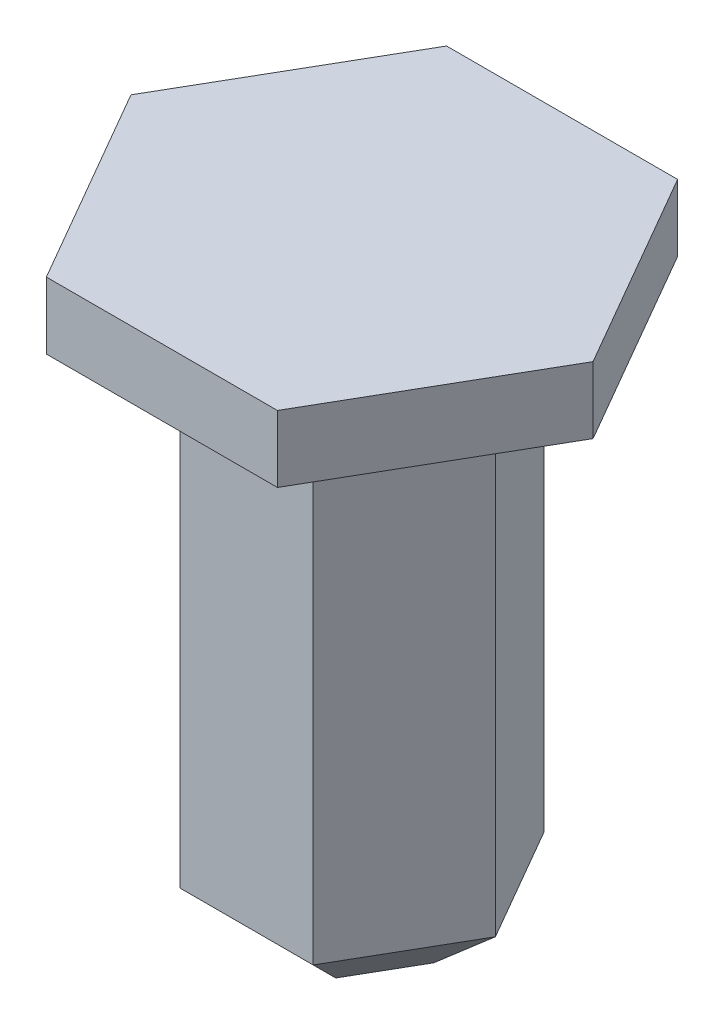
SolidWorks part; units mm, degrees
ref_plane "Front Plane" through (0, 0, 0) normal (0, 0, 1) x (1, 0, 0)
ref_plane "Top Plane" through (0, 0, 0) normal (0, 1, 0) x (1, 0, 0)
ref_plane "Right Plane" through (0, 0, 0) normal (1, 0, 0) x (0, 0, -1)
sketch "Sketch1" plane through (0, 0, 0) normal (0, 1, 0) x (1, 0, 0)
  line L1 (2, 0) -> (1, 1.7321)
  line L2 (1, 1.7321) -> (-1, 1.7321)
  line L3 (-1, 1.7321) -> (-2, 0)
  line L4 (-2, 0) -> (-1, -1.7321)
  line L5 (-1, -1.7321) -> (1, -1.7321)
  line L6 (1, -1.7321) -> (2, 0)
  circle A0 centre (0, 0) radius 2 construction
  circle A1 centre (0, 0) radius 1.7321 construction
  point P3 (0, 0)
  dimension "D1" = 4
extrude "Boss-Extrude1" add sketch "Sketch1" along normal blind 8
chamfer "Chamfer2" distance 0.8 angle 45 6 edges at (1.5, 0, -0.866) (0, 0, -1.7321) (-1.5, 0, -0.866) (-1.5, 0, 0.866) (0, 0, 1.7321) (1.5, 0, 0.866)
sketch "Sketch2" plane through (0, 8, 0) normal (0, 1, 0) x (1, 0, 0)
  line L1 (-3.4641, 0) -> (-1.7321, -3)
  line L2 (-1.7321, -3) -> (1.7321, -3)
  line L3 (1.7321, -3) -> (3.4641, 0)
  line L4 (3.4641, 0) -> (1.7321, 3)
  line L5 (1.7321, 3) -> (-1.7321, 3)
  line L6 (-1.7321, 3) -> (-3.4641, 0)
  circle A0 centre (0, 0) radius 3 construction
  dimension "D1" = 6
extrude "Boss-Extrude2" add sketch "Sketch2" along normal blind 1
